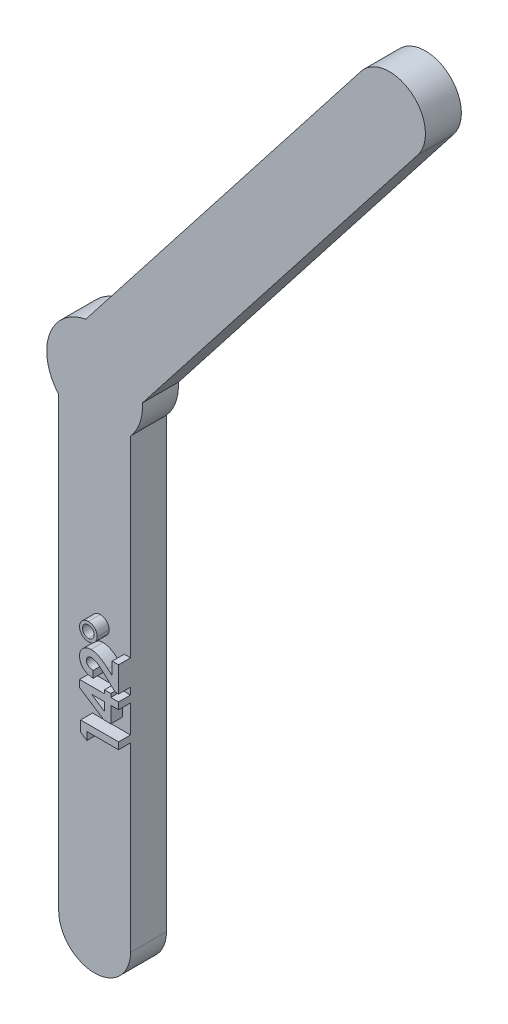
SolidWorks part; units mm, degrees
ref_plane "Front Plane" through (0, 0, 0) normal (0, 0, 1) x (1, 0, 0)
ref_plane "Top Plane" through (0, 0, 0) normal (0, 1, 0) x (1, 0, 0)
ref_plane "Right Plane" through (0, 0, 0) normal (1, 0, 0) x (0, 0, -1)
sketch "Sketch2" plane through (0, 0, 0) normal (0, 0, 1) x (1, 0, 0)
  line L0 (0, 0) -> (0, -40) construction
  line L1 (0, 0) -> (24.6265, 31.5204) construction
  line L2 (22.2624, 33.3674) -> (26.9905, 29.6734) construction
  line L3 (-3, -40) -> (3, -40) construction
  line L4 (-3, -40) -> (-3, -2.6458)
  line L5 (3, -40) -> (3, -2.6458)
  line L6 (22.2624, 33.3674) -> (-0.7351, 3.9319)
  line L7 (26.9905, 29.6734) -> (3.9929, 0.2379)
  arc A0 (-0.7351, 3.9319) -> (-3, -2.6458) centre (0, 0) ccw
  arc A1 (-3, -40) -> (3, -40) centre (0, -40) ccw
  arc A2 (22.2624, 33.3674) -> (26.9905, 29.6734) centre (24.6265, 31.5204) cw
  arc A3 (3, -2.6458) -> (3.9929, 0.2379) centre (0, 0) ccw
  point P12 (24.6265, 31.5204)
  dimension "D3" = 3
  dimension "D4" = 8
  dimension "D1" = 40
  dimension "D2" = 142
extrude "Boss-Extrude1" add sketch "Sketch2" along normal blind 3
sketch "Sketch3" plane through (0, 0, 3) normal (0, 0, 1) x (1, 0, 0)
  text T0 "<b>142°</b>"
extrude "Boss-Extrude2" add sketch "Sketch3" along normal blind 1
